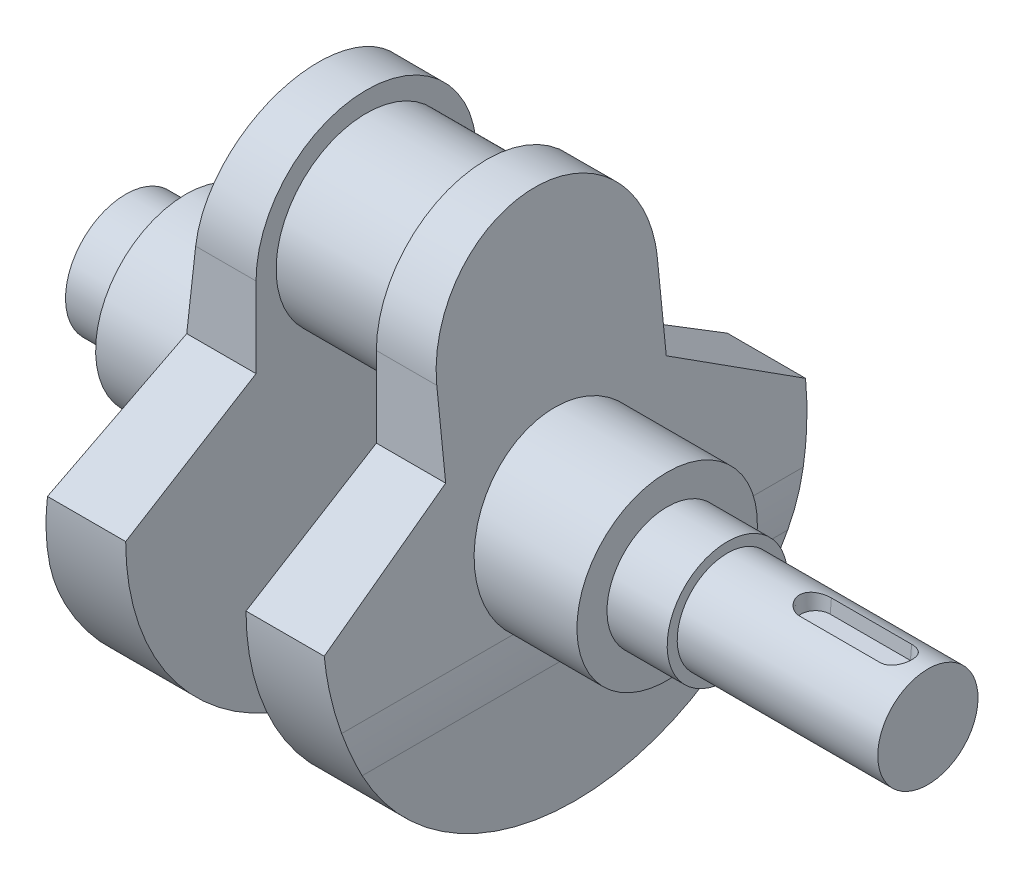
SolidWorks part; units mm, degrees
ref_plane "Front Plane" through (0, 0, 0) normal (0, 0, 1) x (1, 0, 0)
ref_plane "Top Plane" through (0, 0, 0) normal (0, 1, 0) x (1, 0, 0)
ref_plane "Right Plane" through (0, 0, 0) normal (1, 0, 0) x (0, 0, -1)
sketch "Sketch2" plane through (0, 0, 0) normal (1, 0, 0) x (0, 0, -1)
  circle A0 centre (0, 0) radius 22.5
  dimension "D1" = 45
extrude "Boss-Extrude1" add sketch "Sketch2" along normal blind 15
sketch "Sketch3" plane through (15, 0, 0) normal (1, 0, 0) x (0, 0, -1)
  line L0 (-27.5, 0) -> (-27.5, -20)
  line L1 (-27.5, -20) -> (-60, -40)
  line L2 (0, -69.0647) -> (0, 39.4243) construction
  line L3 (27.5, -20) -> (60, -40)
  line L4 (27.5, 0) -> (27.5, -20)
  arc A0 (27.5, 0) -> (-27.5, 0) centre (0, 0) ccw
  arc A1 (-60, -40) -> (60, -40) centre (0, -40) ccw
  dimension "D1" = 120
  dimension "D3" = 55
  dimension "D2" = 40
  dimension "D4" = 20
  dimension "D5" = 40
extrude "Boss-Extrude2" add sketch "Sketch3" along normal blind 22
sketch "Sketch6" plane through (0, 0, 0) normal (0, 0, 1) x (1, 0, 0)
  line L0 (37, 27.5) -> (27, 27.5)
  line L1 (37, 27.5) -> (15, 27.5) construction
  line L2 (27, 27.5) -> (37, -62.5)
  line L3 (37, -100) -> (37, -40) construction
  line L4 (37, -62.5) -> (37, 27.5)
  dimension "D1" = 10
  dimension "D2" = 90
extrude "Cut-Extrude1" cut sketch "Sketch6" against normal through all both and the other way through all
fillet "Fillet1" radius 100 1 edges at (37, -62.5, 0)
sketch "Sketch8" plane through (0, 0, 0) normal (0, 0, 1) x (1, 0, 0)
  line L0 (37, -100) -> (37, 0) construction
  line L1 (37, -100) -> (37, -68.0385) construction
  line L2 (37, 0) -> (-8.9258, 0) construction
  line L3 (32, -17.5) -> (60, -17.5)
  line L4 (60, -17.5) -> (60, -25)
  line L5 (60, -25) -> (75, -25)
  line L6 (75, -25) -> (75, -27.5)
  line L7 (75, -27.5) -> (125, -27.5)
  line L8 (125, -27.5) -> (125, -40)
  line L9 (125, -40) -> (32, -40)
  line L10 (32, -40) -> (32, -17.5)
  line L11 (32, -40) -> (0.724, -40) construction
  line L12 (32.2778, -20) -> (30.0556, 0) construction
  dimension "D1" = 40
  dimension "D2" = 45
  dimension "D3" = 30
  dimension "D4" = 25
  dimension "D5" = 60
  dimension "D6" = 50
  dimension "D7" = 15
revolve "Revolve1" add sketch "Sketch8" angle 360 about L9
sketch "Sketch9" plane through (0, 0, 0) normal (0, 1, 0) x (1, 0, 0)
  line L0 (125, 0) -> (81.1822, 0) construction
  line L1 (125, -12.5) -> (125, 12.5) construction
  line L2 (117, 0) -> (97, 0) construction
  line L3 (117, -4) -> (97, -4)
  line L4 (117, 4) -> (97, 4)
  arc A0 (117, -4) -> (117, 4) centre (117, 0) ccw
  arc A1 (97, 4) -> (97, -4) centre (97, 0) ccw
  point P7 (107, 0)
  dimension "D2" = 4
  dimension "D1" = 20
  dimension "D3" = 8
extrude "Cut-Extrude2" cut sketch "Sketch9" against normal blind 4 draft 5 and the other way through all from offset 27.5 offset against normal yes
mirror "Mirror1" about plane through (0, 0, 0) normal (1, 0, 0) of bodies 105
sketch "Sketch10" plane through (0, 0, 0) normal (0, 0, 1) x (1, 0, 0)
  line L0 (-75, -74.4184) -> (-75, 5.3043)
extrude "Cut-Extrude3" cut sketch "Sketch10" against normal through all and the other way through all
